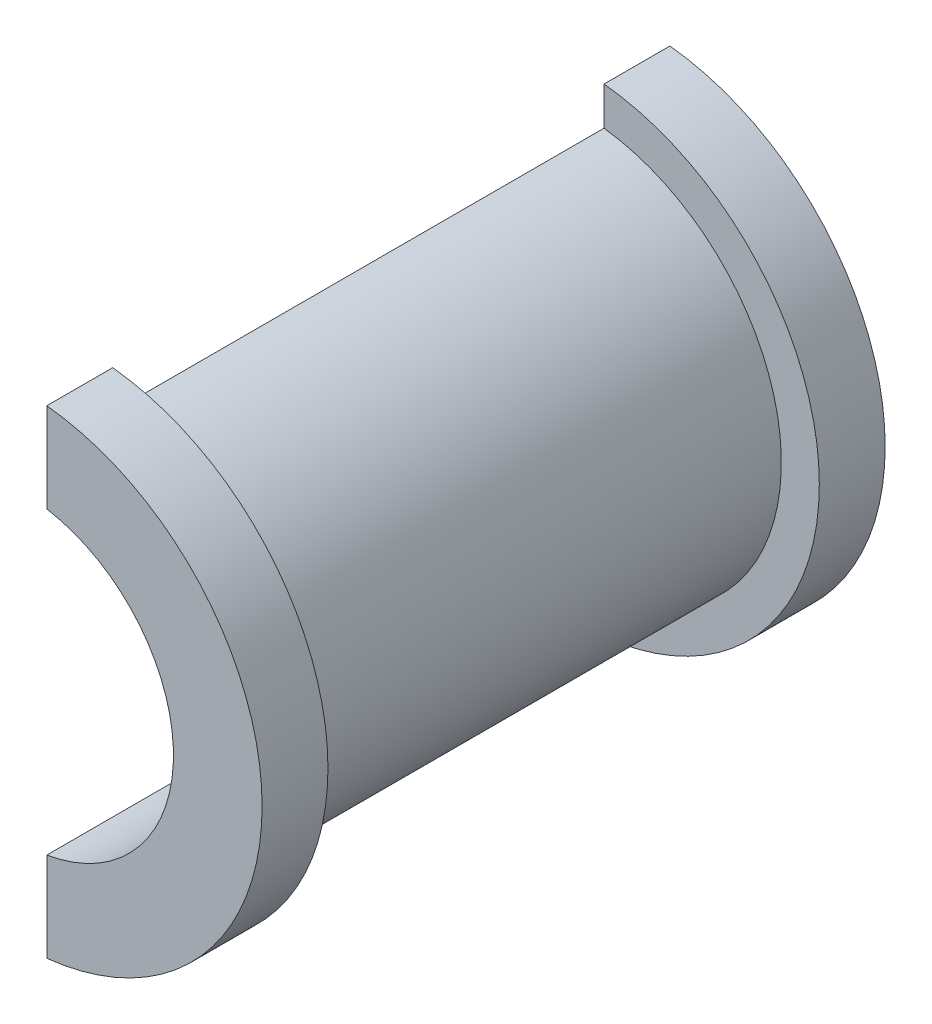
SolidWorks part; units mm, degrees
ref_plane "Front Plane" through (0, 0, 0) normal (0, 0, 1) x (1, 0, 0)
ref_plane "Top Plane" through (0, 0, 0) normal (0, 1, 0) x (1, 0, 0)
ref_plane "Right Plane" through (0, 0, 0) normal (1, 0, 0) x (0, 0, -1)
sketch "Sketch1" plane through (0, 0, 0) normal (0, 0, 1) x (1, 0, 0)
  line L0 (5, 29.5804) -> (5, 39.6863)
  line L1 (5, -29.5804) -> (5, -39.6863)
  line L2 (0, 0) -> (0, 153.1467) construction
  arc A0 (5, 29.5804) -> (5, -29.5804) centre (0, 0) cw
  arc A1 (5, 39.6863) -> (5, -39.6863) centre (0, 0) cw
  dimension "D3" = 30
  dimension "D4" = 40
  dimension "D1" = 5
  dimension "D2" = 5
extrude "Boss-Extrude1" add sketch "Sketch1" along normal mid plane 110
sketch "Sketch2" plane through (0, 0, 55) normal (0, 0, 1) x (1, 0, 0)
  line L0 (5, 29.5804) -> (5, 47.2361)
  line L1 (5, -29.5804) -> (5, -47.2361)
  arc A0 (5, 47.2361) -> (5, -47.2361) centre (0, 0) cw
  arc A1 (5, -29.5804) -> (5, 29.5804) centre (0, 0) ccw construction
  arc A2 (5, -29.5804) -> (5, 29.5804) centre (0, 0) ccw
  dimension "D1" = 47.5
extrude "Boss-Extrude2" add sketch "Sketch2" along normal mid plane 13
mirror "Mirror2" about plane through (0, 0, 0) normal (0, 0, 1) of "Boss-Extrude2"
